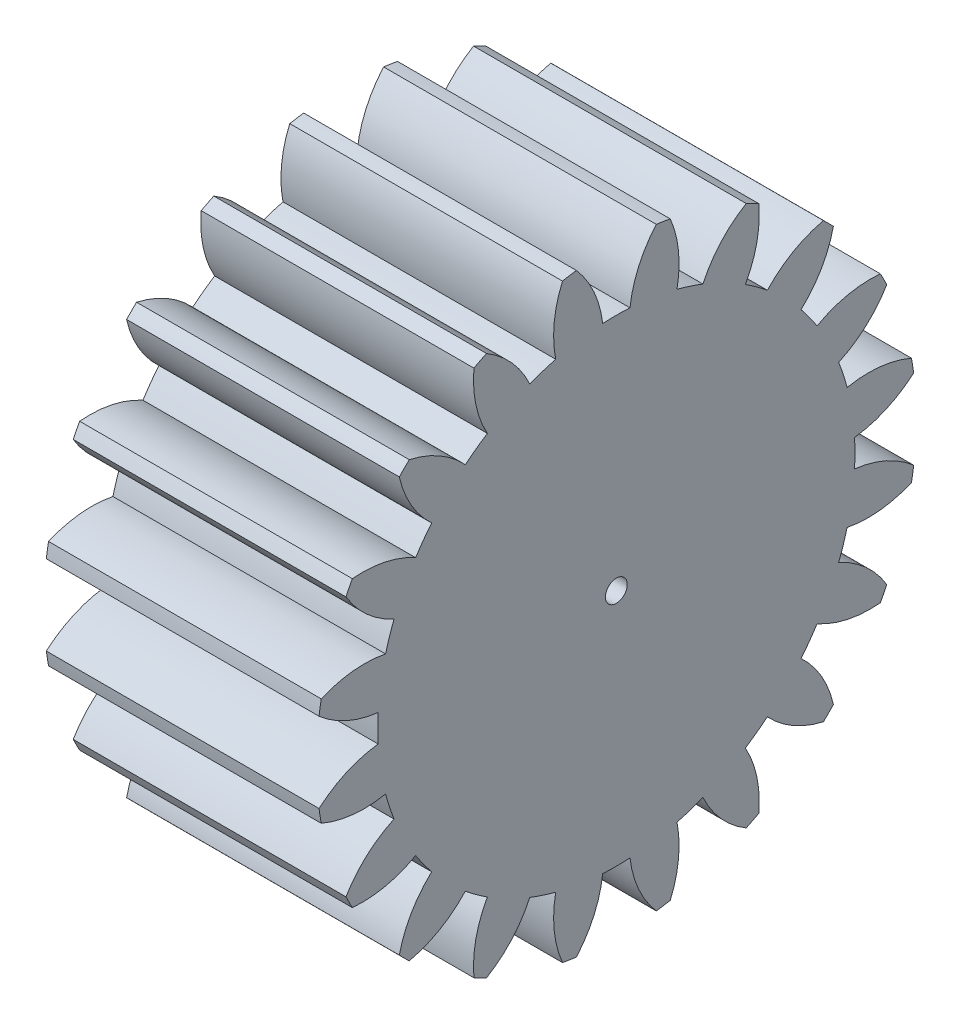
SolidWorks part; units mm, degrees
ref_plane "Plane1" through (0, 0, 0) normal (0, 0, 1) x (1, 0, 0)
ref_plane "Plane2" through (0, 0, 0) normal (0, 1, 0) x (1, 0, 0)
ref_plane "Plane3" through (0, 0, 0) normal (1, 0, 0) x (0, 0, -1)
sketch "HoldingSke" plane through (0, 0, 0) normal (0, 1, 0) x (1, 0, 0)
  line L0 (0, 0) -> (0.9397, -0.342)
  line L1 (-15, 0) -> (100, 0) construction
  line L2 (0, 0) -> (-2.1039, 2.3779)
  line L3 (0, 0) -> (-11.863, 4.5341)
  line L4 (0, 0) -> (8.1152, 2.9537)
  line L5 (0, 0) -> (-46.8476, -17.4728)
  line L6 (0, 0) -> (-4.9738, -3.3558)
  line L7 (-2.1039, 2.3779) -> (8.6586, 51.2059)
  line L8 (-76.2, 54.61) -> (-76.1, 54.61)
  line L9 (-71.009, 38.7566) -> (-53.1078, 45.2721)
  line L10 (-76.2, 71.12) -> (104.1128, 71.12)
  line L11 (0, 0) -> (-6, 0)
  line L12 (-76.2, 101.6) -> (-76.162, 101.6)
  line L13 (24.9733, 27.94) -> (52.9518, 28.4284)
  line L14 (24.9733, 27.94) -> (24.9743, 27.94)
  line L15 (24.9733, 27.94) -> (100.4006, 29.5858)
  line L16 (-63.627, -1) -> (-12.827, -1)
  circle A0 centre (0, 0) radius 0.4
  circle A1 centre (0, 0) radius 8.749
  circle A2 centre (0, 0) radius 37.5
  circle A3 centre (0, 0) radius 0.4
  dimension "MHD" = 17.498
  dimension "Hub_dia" = 75
  dimension "Bore" = 0.8
  dimension "MBD" = 0.8
  dimension "Num_teeth" = 20
  dimension "Pitch" = 1
  dimension "Overall_len" = 50
  dimension "Show_teeth" = 20
  dimension "Thickness" = 6
  dimension "OAL" = 50.0001
  dimension "T_dim" = 0.1
  dimension "Ap" = 20
  dimension "H" = 19.05
  dimension "Pitch_radius" = 180.3128
  dimension "Width" = 6
  dimension "Backlash" = 0.038
  dimension "Addendum_fac" = 1
  dimension "Dedendum_fac" = 1.25
  dimension "Clearance_fac" = 0.25
  dimension "Dedendum_add" = 0.001
  dimension "Module" = 1
sketch "BasProSke" plane through (0, 0, 0) normal (0, 1, 0) x (1, 0, 0)
  line L0 (-10, 0) -> (60, 0) construction
  line L1 (0, 0) -> (0, 11)
  line L2 (0, 0) -> (10, 0)
  line L3 (10, 0) -> (10, 11)
  line L4 (10, 11) -> (0, 11)
  dimension "Thickness" = 10
  dimension "Diameter" = 22
revolve "Base-Revolve" add sketch "BasProSke" angle 360 about L0
sketch "TooCutSke" plane through (0, 0, 0) normal (1, 0, 0) x (0, 0, -1)
  line L1 (0, 0) -> (0, 107) construction
  line L2 (0, 0) -> (-0.8511, 9.9637) construction
  line L3 (0, 0) -> (-3.1206, 19.7028) construction
  line L4 (-0.8511, 9.9637) -> (-1.5603, 9.8514) construction
  arc A0 (0.4999, 8.7347) -> (-0.4999, 8.7347) centre (0, 0) ccw
  arc A1 (1.4852, 10.9249) -> (-1.4852, 10.9249) centre (0, 0) ccw
  circle A2 centre (0, 0) radius 10 construction
  circle A3 centre (0, 0) radius 9.3969 construction
  arc A4 (-0.4999, 8.7347) -> (-1.4852, 10.9249) centre (-4.4722, 8.2645) ccw
  arc A5 (1.4852, 10.9249) -> (0.4999, 8.7347) centre (4.4722, 8.2645) ccw
  dimension "Root_dia" = 17.498
  dimension "Overcut_dia" = 22.0508
  dimension "Pitch_dia" = 20
  dimension "Base_dia" = 18.7939
  dimension "Flank_rad" = 4
  dimension "Half_ang" = 9
  dimension "Half_CT" = 0.7181
extrude "ToothCut" cut sketch "TooCutSke" along normal through all
fillet "Breaks" [suppressed] radius 0.02
fillet "RootFillets" [suppressed] radius 0.251
pattern_circular "TeethCuts" count 20 every 18 about axis through (-10, 0, 0) along (1, 0, 0) of "ToothCut", "RootFillets", "Breaks"
sketch "HubNeaOneSke" plane through (0, 0, 0) normal (-1, 0, 0) x (0, 0, 1)
  circle A0 centre (0, 0) radius 8.749
  dimension "Diameter" = 17.498
extrude "HubNearOne" [suppressed] add sketch "HubNeaOneSke" along normal blind 40.0001
sketch "HubNeaBotSke" plane through (0, 0, 0) normal (-1, 0, 0) x (0, 0, 1)
  circle A0 centre (0, 0) radius 8.749
  dimension "Diameter" = 17.498
extrude "HubNearBoth" [suppressed] add sketch "HubNeaBotSke" along normal blind 20
ref_plane "FarPln" through (10, 0, 0) normal (1, 0, 0) x (0, 0, -1)
sketch "HubFarSke" plane through (10, 0, 0) normal (1, 0, 0) x (0, 0, -1)
  circle A0 centre (0, 0) radius 8.749
  dimension "Diameter" = 17.498
extrude "HubFar" [suppressed] add sketch "HubFarSke" along normal blind 20
sketch "BorSke" plane through (0, 0, 0) normal (1, 0, 0) x (0, 0, -1)
  circle A0 centre (0, 0) radius 0.4
  dimension "Diameter" = 0.8
extrude "Bore" cut sketch "BorSke" along normal mid plane 100.0001
sketch "KeySke" plane through (0, 0, 0) normal (1, 0, 0) x (0, 0, -1)
  line L0 (-0.05, 0) -> (-0.05, 0.5)
  line L1 (-0.05, 0.5) -> (0.05, 0.5)
  line L2 (0.05, 0.5) -> (0.05, 0)
  line L3 (0, 0) -> (0, 34) construction
  line L4 (-0.05, 0) -> (0.05, 0)
  dimension "Offset" = 0.5
  dimension "Width" = 0.1
extrude "Keyway" [suppressed] cut sketch "KeySke" along normal mid plane 100.0001
pattern_circular "Keyway2" [suppressed] count 2 every 90 about axis through (-10, 0, 0) along (1, 0, 0)
equation "' \"Module@HoldingSke\" = 6.35"
equation "' \"Num_teeth@HoldingSke\" = 12"
equation "' \"Ap@HoldingSke\" =  20"
equation "' \"Ap@HoldingSke\" = 20"
equation "' \"Width@HoldingSke\" = 0.5 * 25.4"
equation "' \"Hub_dia@HoldingSke\"= 1 * 25.4"
equation "' \"Hub_dia@HoldingSke\" = 1 * 25.4"
equation "' \"Overall_len@HoldingSke\" = 1.0 * 25.4"
equation "' \"Bore@HoldingSke\" = 0.75 * 25.4"
equation "' \"T_dim@HoldingSke\" = 0.1 * 25.4"
equation "' \"Width@KeySke\" = 0.25 * 25.4"
equation "' \"Show_teeth@HoldingSke\" = 13"
equation "' \"Backlash@HoldingSke\" = 0.009 * 25.4"
equation "' \"Addendum_fac@HoldingSke\" = 1.0"
equation "' \"Dedendum_fac@HoldingSke\" = 1.25"
equation "' \"Dedendum_add@HoldingSke\" = 0.00005 * 25.4"
equation "' \"Clearance_fac@HoldingSke\" = 0.25"
equation "\"Pitch@HoldingSke\" = 1 / \"Module@HoldingSke\""
equation "\"Overcut_dia@TooCutSke\" = (\"Num_teeth@HoldingSke\" + 2 * \"Addendum_fac@HoldingSke\") / \"Pitch@HoldingSke\" + 0.002 * 25.4"
equation "\"Pitch_dia@TooCutSke\" = \"Num_teeth@HoldingSke\" / \"Pitch@HoldingSke\""
equation "\"Base_dia@TooCutSke\" = \"Num_teeth@HoldingSke\" / \"Pitch@HoldingSke\" * cos((\"Ap@HoldingSke\"  * 3.14159265 / 180))"
equation "\"Root_dia@TooCutSke\" = (\"Num_teeth@HoldingSke\" + 2) / \"Pitch@HoldingSke\" - 2 * (\"Addendum_fac@HoldingSke\" + \"Dedendum_fac@HoldingSke\") / \"Pitch@HoldingSke\" - \"Dedendum_add@HoldingSke\" * 2"
equation "\"Half_ang@TooCutSke\" = 180 / \"Num_teeth@HoldingSke\""
equation "\"Half_CT@TooCutSke\" = \"Num_teeth@HoldingSke\" / \"Pitch@HoldingSke\" * sin((3.14159265 / 2 / \"Num_teeth@HoldingSke\")) / 2 - 7 * \"Backlash@HoldingSke\" / 4"
equation "\"Flank_rad@TooCutSke\" = \"Num_teeth@HoldingSke\" / \"Pitch@HoldingSke\" / 5"
equation "\"Radius@RootFillets\" = \"Clearance_fac@HoldingSke\" / \"Pitch@HoldingSke\" + \"Dedendum_add@HoldingSke\""
equation "\"Break_rad@Breaks\" = 0.02 / \"Pitch@HoldingSke\""
equation "\"Thickness@HoldingSke\" = \"Width@HoldingSke\""
equation "\"OAL@HoldingSke\" = \"Thickness@HoldingSke\""
equation "\"MHD@HoldingSke\" = (\"Num_teeth@HoldingSke\" + 2) / \"Pitch@HoldingSke\" - 2 * (\"Addendum_fac@HoldingSke\" + \"Dedendum_fac@HoldingSke\")  / \"Pitch@HoldingSke\" - \"Dedendum_add@HoldingSke\" * 2"
equation "\"MBD@HoldingSke\" = (\"Num_teeth@HoldingSke\" + 2) / \"Pitch@HoldingSke\" - 2 * (\"Addendum_fac@HoldingSke\" + \"Dedendum_fac@HoldingSke\")  / \"Pitch@HoldingSke\" - \"Dedendum_add@HoldingSke\" * 2 - 0.002 * 25.4"
equation "\"MHD@HoldingSke\" = ((sgn( \"MHD@HoldingSke\" - \"Hub_dia@HoldingSke\" )-1)*( \"MHD@HoldingSke\" - \"Hub_dia@HoldingSke\" ))/-2+ \"Hub_dia@HoldingSke\""
equation "\"MBD@HoldingSke\" = ((sgn( \"MBD@HoldingSke\" - \"Bore@HoldingSke\" )-1)*( \"MBD@HoldingSke\" - \"Bore@HoldingSke\" ))/-2+ \"Bore@HoldingSke\""
equation "\"OAL@HoldingSke\" = ((sgn( \"OAL@HoldingSke\" - \"Overall_len@HoldingSke\" )+1)*( \"OAL@HoldingSke\" - \"Overall_len@HoldingSke\" ))/2 + \"Overall_len@HoldingSke\" + 0.000002 * 25.4"
equation "\"Num_teeth@TeethCuts\" = int( \"Show_teeth@HoldingSke\" ) + 1"
equation "\"Num_teeth@TeethCuts\" = ((sgn( \"Num_teeth@TeethCuts\" - \"Num_teeth@HoldingSke\" )-1)*( \"Num_teeth@TeethCuts\" - \"Num_teeth@HoldingSke\" ))/-2+ \"Num_teeth@HoldingSke\""
equation "\"Num_teeth@TeethCuts\" = ((sgn( \"Num_teeth@TeethCuts\" - 2.0)+1)*( \"Num_teeth@TeethCuts\" - 2.0))/2 +2.0"
equation "\"Angle@TeethCuts\" = 360.0 / \"Num_teeth@HoldingSke\""
equation "\"Diameter@BasProSke\" = (\"Num_teeth@HoldingSke\" + 2 * \"Addendum_fac@HoldingSke\") / \"Pitch@HoldingSke\""
equation "' \"Fillet_rad@BasProSke\" =  \"Thickness@HoldingSke\" * 0.05"
equation "' \"Fillet_rad@BasProSke\" = \"Thickness@HoldingSke\" * 0.05"
equation "\"MHD@HoldingSke\" = ((sgn( \"MHD@HoldingSke\" - \"Root_dia@TooCutSke\" )-1)*( \"MHD@HoldingSke\" - \"Root_dia@TooCutSke\" ))/-2+ \"Root_dia@TooCutSke\""
equation "\"Diameter@HubNeaOneSke\" = \"MHD@HoldingSke\""
equation "\"Length@HubNearOne\" = \"OAL@HoldingSke\" - \"Thickness@BasProSke\""
equation "\"Diameter@HubNeaBotSke\" = \"MHD@HoldingSke\""
equation "\"Length@HubNearBoth\" = ( \"OAL@HoldingSke\" - \"Thickness@BasProSke\" ) / 2.0"
equation "\"Thickness@FarPln\" = \"Thickness@BasProSke\""
equation "\"Diameter@HubFarSke\" = \"MHD@HoldingSke\""
equation "\"Length@HubFar\" = ( \"OAL@HoldingSke\" - \"Thickness@BasProSke\" ) / 2.0"
equation "\"Diameter@BorSke\" = \"MBD@HoldingSke\""
equation "\"D1@Bore\" = \"OAL@HoldingSke\" * 2.0"
equation "\"D1@Keyway\" = \"OAL@HoldingSke\" * 2.0"
equation "\"Offset@KeySke\" = \"T_dim@HoldingSke\" + \"MBD@HoldingSke\" / 2.0"
